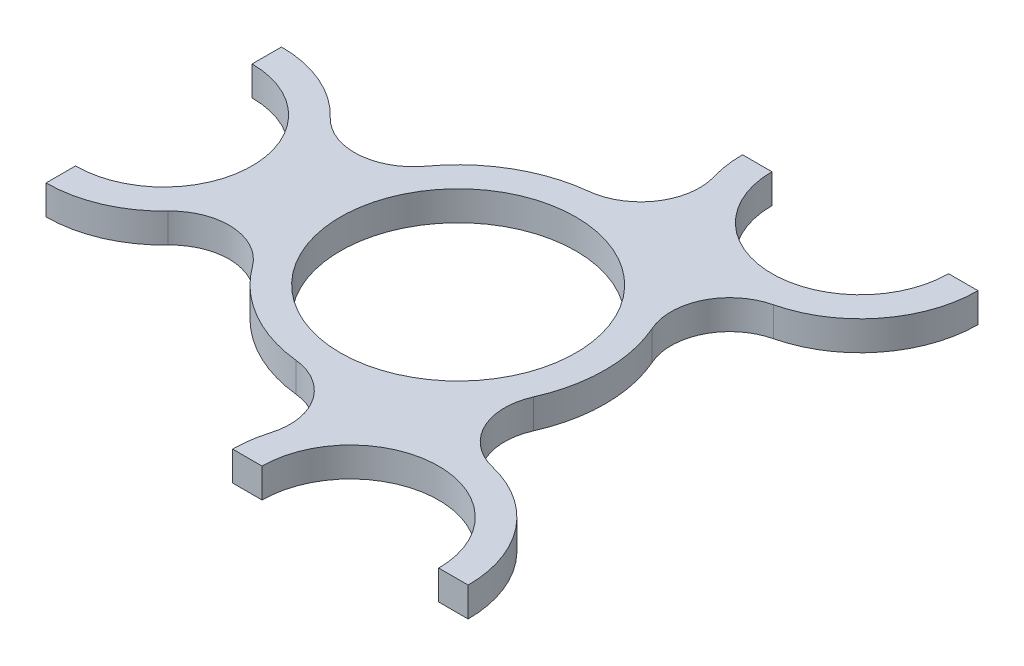
SolidWorks part; units mm, degrees
ref_plane "Ön Düzlem" through (0, 0, 0) normal (0, 0, 1) x (1, 0, 0)
ref_plane "Üst Düzlem" through (0, 0, 0) normal (0, 1, 0) x (1, 0, 0)
ref_plane "Sağ Düzlem" through (0, 0, 0) normal (1, 0, 0) x (0, 0, -1)
sketch "Çizim1" plane through (0, 0, 0) normal (0, 1, 0) x (1, 0, 0)
  line L0 (-100, -40) -> (-100, -30)
  line L1 (-100, 30) -> (-100, 40)
  line L2 (10, 86.6) -> (20, 86.6)
  line L3 (80, 86.6) -> (90, 86.6)
  line L4 (10, -86.6) -> (20, -86.6)
  line L5 (80, -86.6) -> (90, -86.6)
  circle A0 centre (0, 0) radius 40
  arc A1 (-5.3851, 49.7092) -> (-40.3571, 29.5178) centre (0, 0) ccw
  arc A2 (-100, -30) -> (-100, 30) centre (-100, 0) ccw
  arc A3 (-71, 27.55) -> (-100, 40) centre (-100, 0) ccw
  arc A4 (20, 86.6) -> (80, 86.6) centre (50, 86.6) ccw
  arc A5 (59.3596, 47.7104) -> (90, 86.6) centre (50, 86.6) ccw
  arc A6 (59.3596, -47.7104) -> (90, -86.6) centre (50, -86.6) cw
  arc A7 (20, -86.6) -> (80, -86.6) centre (50, -86.6) cw
  arc A8 (59.3596, 47.7104) -> (45.7425, 20.1898) centre (64.0395, 28.2657) ccw
  arc A9 (45.7425, -20.1898) -> (59.3596, -47.7104) centre (64.0395, -28.2657) ccw
  arc A10 (-40.3571, -29.5178) -> (-71, -27.55) centre (-56.5, -41.3249) ccw
  arc A11 (-71, 27.55) -> (-40.3571, 29.5178) centre (-56.5, 41.3249) ccw
  arc A12 (11.6406, -75.2619) -> (-5.3851, -49.7092) centre (-7.5392, -69.5928) ccw
  arc A13 (-5.3851, 49.7092) -> (11.6406, 75.2619) centre (-7.5392, 69.5928) ccw
  arc A14 (-40.3571, -29.5178) -> (-5.3851, -49.7092) centre (0, 0) ccw
  arc A15 (45.7425, -20.1898) -> (45.7425, 20.1898) centre (0, 0) ccw
  arc A16 (-100, -40) -> (-71, -27.55) centre (-100, 0) ccw
  arc A17 (10, 86.6) -> (11.6406, 75.2619) centre (50, 86.6) ccw
  arc A18 (10, -86.6) -> (11.6406, -75.2619) centre (50, -86.6) cw
  dimension "D1" = 80
  dimension "D2" = 100
  dimension "D3" = 60
  dimension "D4" = 80
  dimension "D5" = 60
  dimension "D6" = 80
  dimension "D10" = 40
  dimension "D7" = 100
  dimension "D8" = 50
  dimension "D9" = 86.6
extrude "Yükseklik-Ekstrüzyon1" add sketch "Çizim1" along normal blind 10
